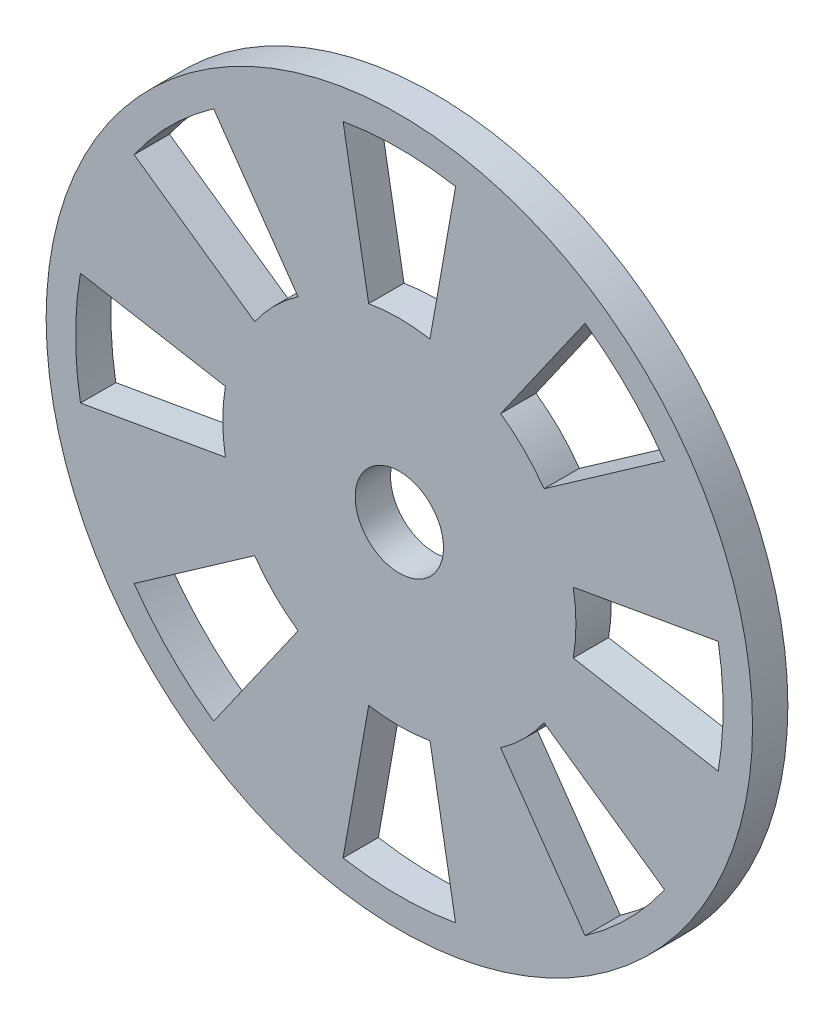
SolidWorks part; units mm, degrees
ref_plane "Front Plane" through (0, 0, 0) normal (0, 0, 1) x (1, 0, 0)
ref_plane "Top Plane" through (0, 0, 0) normal (0, 1, 0) x (1, 0, 0)
ref_plane "Right Plane" through (0, 0, 0) normal (1, 0, 0) x (0, 0, -1)
sketch "Sketch2" plane through (0, 0, 0) normal (0, 0, 1) x (1, 0, 0)
  circle A0 centre (0, 0) radius 12
  circle A1 centre (0, 0) radius 1.5
  dimension "D1" = 3
  dimension "D2" = 24
extrude "Boss-Extrude1" add sketch "Sketch2" along normal blind 1.2
sketch "Sketch3" plane through (0, 0, 1.2) normal (0, 0, 1) x (1, 0, 0)
  line L0 (0, 0) -> (0, 12) construction
  line L1 (0, 0) -> (1.9101, 10.8329)
  line L2 (0, 0) -> (-1.9101, 10.8329)
  circle A0 centre (0, 0) radius 6
  circle A2 centre (0, 0) radius 11
  dimension "D1" = 12
  dimension "D2" = 22
  dimension "D3" = 10
  dimension "D4" = 10
extrude "Cut-Extrude1" cut sketch "Sketch3" against normal blind 1.2 contours A0 L0 A2 L2 | L0 A0 L1 A2
pattern_circular "CirPattern1" count 8 over 360 about axis through (0, 0, 0) along (0, 0, 1) of "Cut-Extrude1"
